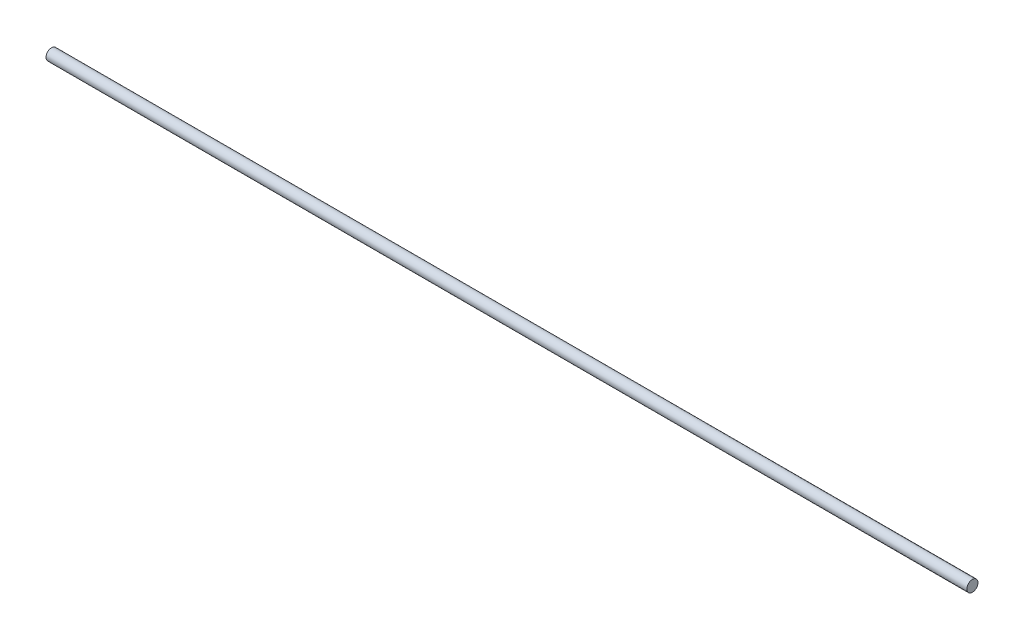
SolidWorks part; units mm, degrees
ref_plane "Front Plane" through (0, 0, 0) normal (0, 0, 1) x (1, 0, 0)
ref_plane "Top Plane" through (0, 0, 0) normal (0, 1, 0) x (1, 0, 0)
ref_plane "Right Plane" through (0, 0, 0) normal (1, 0, 0) x (0, 0, -1)
sketch "Sketch2" plane through (0, 0, 0) normal (1, 0, 0) x (0, 0, -1)
  circle A0 centre (0, 0) radius 1.2
extrude "Boss-Extrude1" add sketch "Sketch2" along normal blind 198.12
